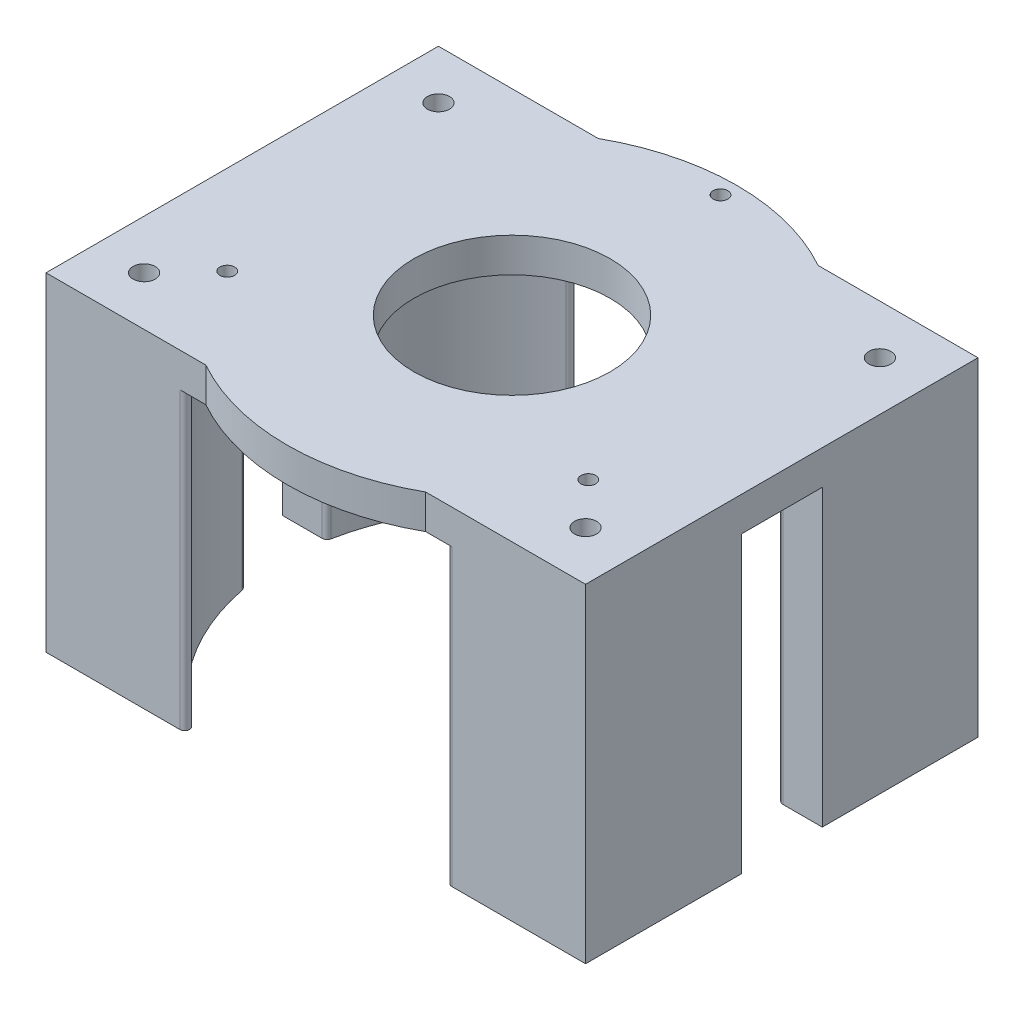
SolidWorks part; units mm, degrees
ref_plane "Front Plane" through (0, 0, 0) normal (0, 0, 1) x (1, 0, 0)
ref_plane "Top Plane" through (0, 0, 0) normal (0, 1, 0) x (1, 0, 0)
ref_plane "Right Plane" through (0, 0, 0) normal (1, 0, 0) x (0, 0, -1)
sketch "Sketch1" plane through (0, 0, 0) normal (0, 1, 0) x (1, 0, 0)
  line L0 (-10, 70) -> (20.609, 70)
  line L1 (0, 60) -> (90, 60) construction
  line L2 (0, 60) -> (0, 43.0354) construction
  line L3 (0, 0) -> (90, 0) construction
  line L4 (90, 60) -> (90, 43.0354) construction
  line L5 (100, 70) -> (100, 38.251)
  line L6 (-10, -10) -> (20.609, -10)
  line L7 (-10, 70) -> (-10, 38.251)
  line L8 (69.391, 70) -> (100, 70)
  line L9 (-10, 70) -> (100, 70) construction
  line L10 (69.391, -10) -> (100, -10)
  line L11 (-10, -10) -> (100, -10) construction
  line L12 (0, 16.9646) -> (0, 0) construction
  line L13 (100, 21.749) -> (91.1177, 21.749)
  line L15 (100, 38.251) -> (91.1177, 38.251)
  line L19 (0, 60) -> (0, 0) construction
  line L20 (-10, 21.749) -> (-10, -10)
  line L21 (-10, 70) -> (-10, -10) construction
  line L22 (-1.1177, 38.251) -> (-10, 38.251)
  line L23 (-1.1177, 21.749) -> (-10, 21.749)
  line L24 (100, 21.749) -> (100, -10)
  line L25 (100, 70) -> (100, -10) construction
  line L26 (90, 16.9646) -> (90, 0) construction
  line L27 (90, 60) -> (90, 0) construction
  circle A0 centre (0, 0) radius 2.25
  circle A1 centre (90, 0) radius 2.25
  circle A2 centre (90, 60) radius 2.25
  circle A3 centre (0, 60) radius 2.25
  arc A5 (20.609, 70) -> (-1.1177, 38.251) centre (45, 30) ccw
  arc A6 (69.391, -10) -> (91.1177, 21.749) centre (45, 30) ccw
  arc A7 (-1.1177, 21.749) -> (20.609, -10) centre (45, 30) ccw
  arc A8 (91.1177, 38.251) -> (69.391, 70) centre (45, 30) ccw
  dimension "D1" = 2
  dimension "D3" = 10
  dimension "D2" = 2
extrude "Boss-Extrude1" add sketch "Sketch1" along normal blind 60 contours A5 L0 L7 L22 A3 | A7 L23 L20 L6 A0 | A8 L15 L5 L8 A2 | A6 L10 L24 L13 A1
sketch "Sketch2" plane through (0, 60, 0) normal (0, 1, 0) x (1, 0, 0)
  line L0 (-10, 70) -> (20.609, 70) construction
  line L5 (-10, 70) -> (100, 70)
  line L6 (-10, 70) -> (-10, -10)
  line L7 (-10, -10) -> (100, -10)
  line L8 (100, 70) -> (100, -10)
  line L9 (-10, 70) -> (-10, 38.251) construction
  line L10 (100, 21.749) -> (100, -10) construction
  circle A16 centre (0, 0) radius 2.25 construction
  circle A17 centre (0, 60) radius 2.25 construction
  circle A18 centre (90, 60) radius 2.25 construction
  circle A19 centre (90, 0) radius 2.25 construction
  circle A20 centre (0, 0) radius 2.25
  circle A21 centre (0, 60) radius 2.25
  circle A22 centre (90, 60) radius 2.25
  circle A23 centre (90, 0) radius 2.25
sketch "Sketch5" plane through (0, 60, 0) normal (0, 1, 0) x (1, 0, 0)
  line L0 (69.391, -10) -> (100, -10) construction
  line L1 (-10, 70) -> (22.5897, 70)
  line L2 (-10, 70) -> (-10, -10)
  line L3 (-10, -10) -> (22.5897, -10)
  line L4 (100, 70) -> (100, -10)
  line L5 (100, 21.749) -> (100, -10) construction
  line L6 (67.4103, 70) -> (100, 70)
  line L7 (67.4103, -10) -> (100, -10)
  circle A0 centre (81.8061, 8.75) radius 1.5
  arc A1 (22.5897, -10) -> (67.4103, -10) centre (45, 30) ccw
  circle A2 centre (45, 72.5) radius 1.5
  circle A3 centre (8.1939, 8.75) radius 1.5
  arc A4 (67.4103, 70) -> (22.5897, 70) centre (45, 30) ccw
  circle A5 centre (45, 30) radius 20
  circle A6 centre (90, 60) radius 2.25 construction
  circle A7 centre (90, 0) radius 2.25 construction
  circle A8 centre (0, 0) radius 2.25 construction
  circle A9 centre (0, 60) radius 2.25 construction
  circle A10 centre (90, 60) radius 2.25
  circle A11 centre (90, 0) radius 2.25
  circle A12 centre (0, 0) radius 2.25
  circle A13 centre (0, 60) radius 2.25
  point P11 (45, 30)
  dimension "D1" = 42.5
  dimension "D2" = 3
extrude "Boss-Extrude3" add sketch "Sketch5" along normal blind 7 contours A1 | A2 | A3 | A0 | L2 L3 A1 L7 L4 L6 A4 L1
fillet "Fillet1" radius 1 8 edges at (-1.1177, 30, -38.251) (-1.1177, 30, -21.749) (91.1177, 30, -21.749) (91.1177, 30, -38.251) (69.391, 30, -70) (20.609, 30, -70) (20.609, 30, 10) (69.391, 30, 10)
